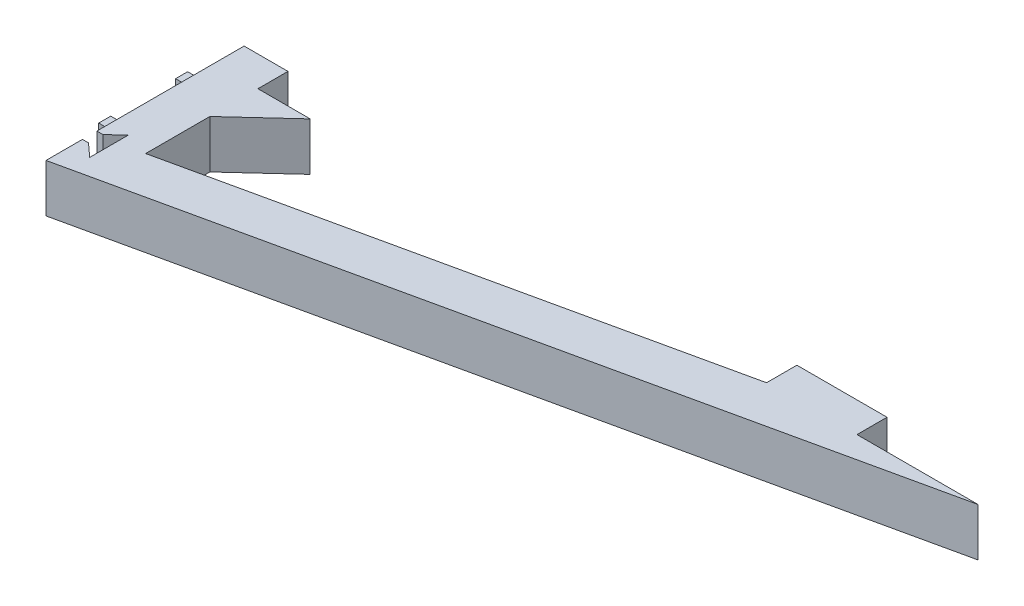
SolidWorks part; units mm, degrees
ref_plane "Přední rovina" through (0, 0, 0) normal (0, 0, 1) x (1, 0, 0)
ref_plane "Horní rovina" through (0, 0, 0) normal (0, 1, 0) x (1, 0, 0)
ref_plane "Pravá rovina" through (0, 0, 0) normal (1, 0, 0) x (0, 0, -1)
sketch "Skica1" plane through (0, 0, 0) normal (0, 1, 0) x (1, 0, 0)
  line L0 (0, 0) -> (0, -32.97)
  line L1 (0, -32.97) -> (127.1408, -5)
  line L2 (127.1408, -5) -> (107, -5)
  line L4 (107, -5) -> (107, 0)
  line L5 (107, 0) -> (92, 0)
  line L6 (92, 0) -> (92, -5.0514)
  line L7 (92, -5.0514) -> (7.3, -23.6847)
  line L8 (7.3, -23.6847) -> (7.3, 0)
  line L9 (7.3, 0) -> (0, 0)
  point P3 (92, -2.5257)
  dimension "D1" = 32.97
  dimension "D2" = 7.3
  dimension "D3" = 15
  dimension "D4" = 5
  dimension "D5" = 7.5
  dimension "D6" = 77.593
  dimension "D7" = 84.7
extrude "Přidat vysunutím1" add sketch "Skica1" along normal blind 8
sketch "Skica2" plane through (0, 8, 0) normal (0, 1, 0) x (1, 0, 0)
  line L6 (0, -24.5) -> (1, -24.5)
  line L7 (0, 0) -> (0, -32.97) construction
  line L8 (1, -24.5) -> (3.2, -22.5)
  line L9 (3.2, -22.5) -> (3.2, -28.9)
  line L10 (3.2, -28.9) -> (1, -26.9)
  line L11 (1, -26.9) -> (0, -26.9)
  line L12 (0, -26.9) -> (0, -24.5)
  line L13 (7.3, 0) -> (0, 0) construction
  dimension "D1" = 1
  dimension "D2" = 1
  dimension "D3" = 3.2
  dimension "6,8" = 6.4
  dimension "2,8" = 2.4
  dimension "D4" = 2
  dimension "4" = 22.5
extrude "Odebrat vysunutím1" cut sketch "Skica2" against normal through all
sketch "Skica3" plane through (0, 0, 0) normal (-1, 0, 0) x (0, 0, 1)
  line L1 (5.4, 5) -> (7.4, 5)
  line L2 (5.4, 5) -> (5.4, 3)
  line L3 (5.4, 3) -> (7.4, 3)
  line L4 (7.4, 5) -> (7.4, 3)
  line L5 (18.2, 5) -> (20.2, 5)
  line L6 (18.2, 5) -> (18.2, 3)
  line L7 (18.2, 3) -> (20.2, 3)
  line L8 (20.2, 5) -> (20.2, 3)
  line L13 (0, 8) -> (0, 0) construction
  line L14 (0, 8) -> (24.5, 8) construction
  dimension "D1" = 2
  dimension "D2" = 2
  dimension "D3" = 2
  dimension "D4" = 2
  dimension "D7" = 5.4
  dimension "D8" = 3
  dimension "D9" = 3
  dimension "D11" = 10.8
extrude "Přidat vysunutím2" add sketch "Skica3" along normal blind 4
sketch "Skica5" plane through (0, 8, 0) normal (0, 1, 0) x (1, 0, 0)
  line L0 (0, 0) -> (0, -24.5) construction
  line L5 (0, -5) -> (16, -5)
  line L6 (0, -5) -> (0, -13)
  line L7 (0, -13) -> (16, -13)
  line L8 (16, -5) -> (16, -13)
  line L9 (7.3, 0) -> (0, 0) construction
  dimension "D1" = 8
  dimension "D2" = 5
  dimension "D3" = 16
extrude "Přidat vysunutím4" add sketch "Skica5" against normal blind 8
sketch "Skica7" plane through (0, 0, 0) normal (0, -1, 0) x (1, 0, 0)
  line L3 (7.3, 13) -> (16, 13)
  line L4 (16, 13) -> (16, 5)
  line L5 (16, 5) -> (7.3, 13)
extrude "Odebrat vysunutím3" cut sketch "Skica7" against normal through all
